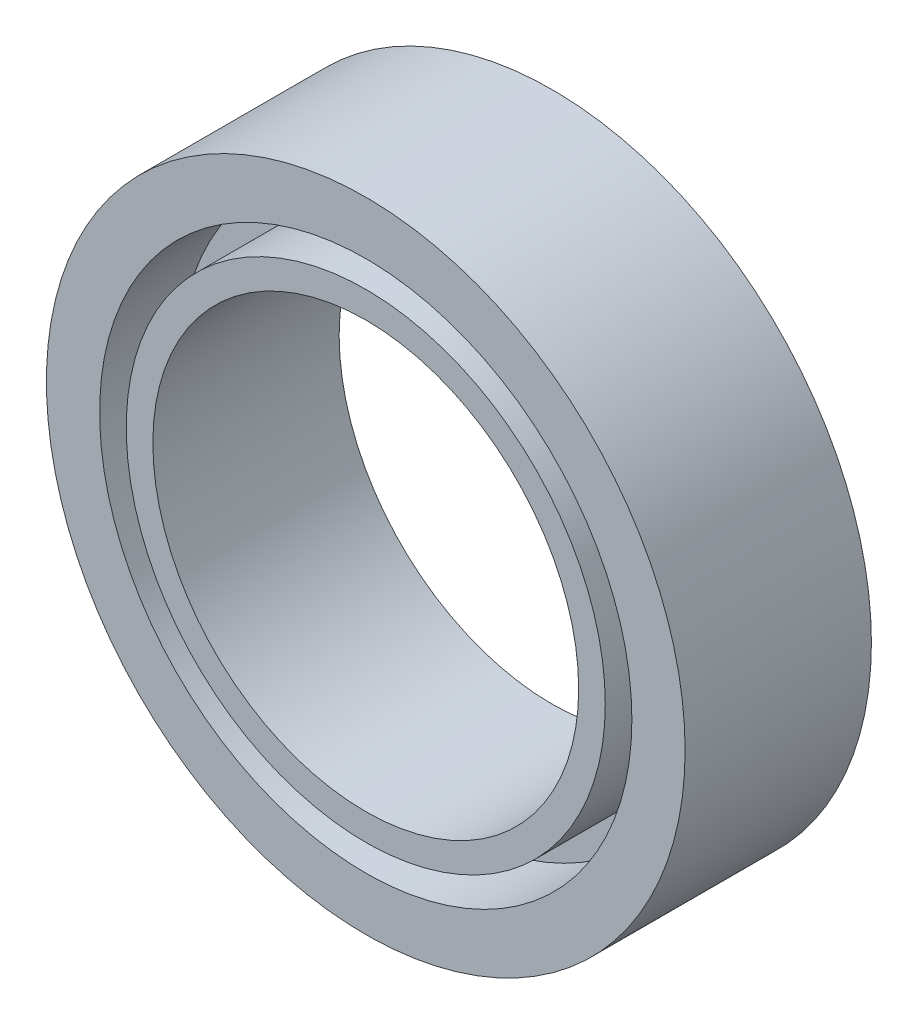
SolidWorks part; units mm, degrees
ref_plane "前视基准面" through (0, 0, 0) normal (0, 0, 1) x (1, 0, 0)
ref_plane "上视基准面" through (0, 0, 0) normal (0, 1, 0) x (1, 0, 0)
ref_plane "右视基准面" through (0, 0, 0) normal (1, 0, 0) x (0, 0, -1)
sketch "草图1" plane through (0, 0, 0) normal (0, 0, 1) x (1, 0, 0)
  circle A0 centre (0, 0) radius 4
  circle A1 centre (0, 0) radius 6
  dimension "D1" = 8
  dimension "D2" = 12
extrude "凸台-拉伸1" add sketch "草图1" along normal blind 3.5
ref_plane "基准面1" through (0, 0, 1.75) normal (0, 0, 1) x (1, 0, 0)
sketch "草图2" plane through (0, 0, 3.5) normal (0, 0, 1) x (1, 0, 0)
  circle A0 centre (0, 0) radius 4.5
  circle A1 centre (0, 0) radius 5
  dimension "D1" = 9
  dimension "D2" = 10
extrude "切除-拉伸1" cut sketch "草图2" against normal blind 1.5
mirror "镜向1" about plane through (0, 0, 1.75) normal (0, 0, 1) of "切除-拉伸1"
